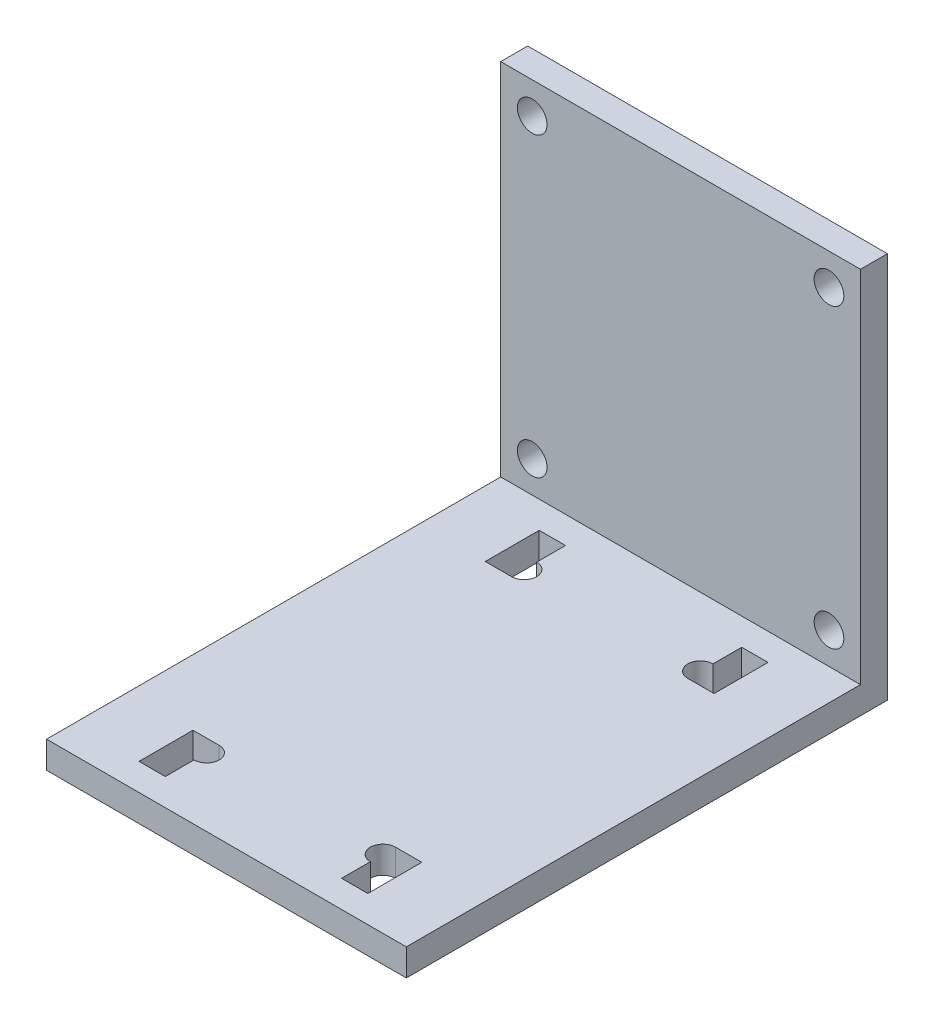
SolidWorks part; units mm, degrees
ref_plane "Front Plane" through (0, 0, 0) normal (0, 0, 1) x (1, 0, 0)
ref_plane "Top Plane" through (0, 0, 0) normal (0, 1, 0) x (1, 0, 0)
ref_plane "Right Plane" through (0, 0, 0) normal (1, 0, 0) x (0, 0, -1)
sketch "Sketch1" plane through (0, 0, 0) normal (0, 0, 1) x (1, 0, 0)
  line L1 (0, 0) -> (40, 0)
  line L2 (0, 0) -> (0, 40)
  line L3 (0, 40) -> (40, 40)
  line L4 (40, 0) -> (40, 40)
  dimension "D1" = 40
  dimension "D2" = 40
extrude "Boss-Extrude1" add sketch "Sketch1" along normal blind 3
sketch "Sketch2" plane through (0, 0, 3) normal (0, 0, 1) x (1, 0, 0)
  line L0 (40, 40) -> (0, 40) construction
  line L1 (0, 40) -> (0, 0) construction
  line L2 (-1000, 20) -> (49000, 20) construction
  line L3 (20, -1000) -> (20, 49000) construction
  line L4 (0, 0) -> (40, 0) construction
  circle A0 centre (3.5, 36.5) radius 1.65
  circle A1 centre (36.5, 36.5) radius 1.65
  circle A2 centre (36.5, 3.5) radius 1.65
  circle A3 centre (3.5, 3.5) radius 1.65
  point P9 (0, 20)
  point P13 (20, 0)
  dimension "D1" = 3.3
  dimension "D2" = 3.5
  dimension "D3" = 3.5
extrude "Cut-Extrude1" cut sketch "Sketch2" against normal blind 3
sketch "Sketch3" plane through (0, 0, 3) normal (0, 0, 1) x (1, 0, 0)
  line L0 (40, 0) -> (40, 40) construction
  line L1 (0, 0) -> (40, 0)
  line L2 (0, 0) -> (0, -3)
  line L3 (0, -3) -> (40, -3)
  line L4 (40, 0) -> (40, -3)
  dimension "D1" = 3
extrude "Boss-Extrude2" add sketch "Sketch3" against normal blind 3
sketch "Sketch4" plane through (0, -3, 0) normal (0, -1, 0) x (1, 0, 0)
  line L0 (4.1, 50.5) -> (35.9, 50.5) construction
  line L1 (4.1, 50.5) -> (4.1, 6) construction
  line L2 (4.1, 6) -> (35.9, 6) construction
  line L3 (35.9, 50.5) -> (35.9, 6) construction
  line L4 (7.28, 50.5) -> (10.2, 50.5)
  line L5 (7.28, 50.5) -> (7.28, 44.5)
  line L6 (7.28, 44.5) -> (10.2, 44.5)
  line L7 (10.2, 50.5) -> (10.2, 47.3)
  line L8 (20, -963.4982) -> (20, 49036.5018) construction
  line L9 (-997.5058, 28.25) -> (49002.4942, 28.25) construction
  line L10 (32.72, 50.5) -> (32.72, 44.5)
  line L11 (32.72, 44.5) -> (29.8, 44.5)
  line L12 (29.8, 50.5) -> (29.8, 47.3)
  line L13 (32.72, 50.5) -> (29.8, 50.5)
  line L14 (32.72, 6) -> (29.8, 6)
  line L15 (29.8, 6) -> (29.8, 9.2)
  line L16 (32.72, 12) -> (29.8, 12)
  line L17 (32.72, 6) -> (32.72, 12)
  line L18 (7.28, 6) -> (7.28, 12)
  line L19 (7.28, 12) -> (10.2, 12)
  line L20 (10.2, 6) -> (10.2, 9.2)
  line L21 (7.28, 6) -> (10.2, 6)
  line L23 (0, 0) -> (40, 0) construction
  line L25 (0, 3) -> (40, 3)
  line L26 (0, 3) -> (0, 53.5)
  line L27 (0, 53.5) -> (40, 53.5)
  line L28 (40, 3) -> (40, 53.5)
  line L29 (40, 0) -> (40, 3) construction
  arc A0 (10.2, 44.5) -> (10.2, 47.3) centre (10.2, 45.9) ccw
  arc A1 (29.8, 44.5) -> (29.8, 47.3) centre (29.8, 45.9) cw
  arc A2 (29.8, 12) -> (29.8, 9.2) centre (29.8, 10.6) ccw
  arc A3 (10.2, 12) -> (10.2, 9.2) centre (10.2, 10.6) cw
  point P15 (20, 50.5)
  point P16 (4.1, 28.25)
  point P38 (20, 0)
  line M9 (40, 3) -> (0, 3)
  dimension "D5" = 1.4
  dimension "D1" = 44.5
  dimension "D2" = 31.8
  dimension "D3" = 2.92
  dimension "D4" = 6
  dimension "D6" = 3.18
  dimension "D7" = 3
  dimension "D8" = 3
extrude "Boss-Extrude3" add sketch "Sketch4" against normal blind 3 contours L19 A3 L20 L15 A2 L16 L17 L28 L27 L26 L18 A0 L6 L5 L4 L7 L11 A1 L12 L13 L10 M9
